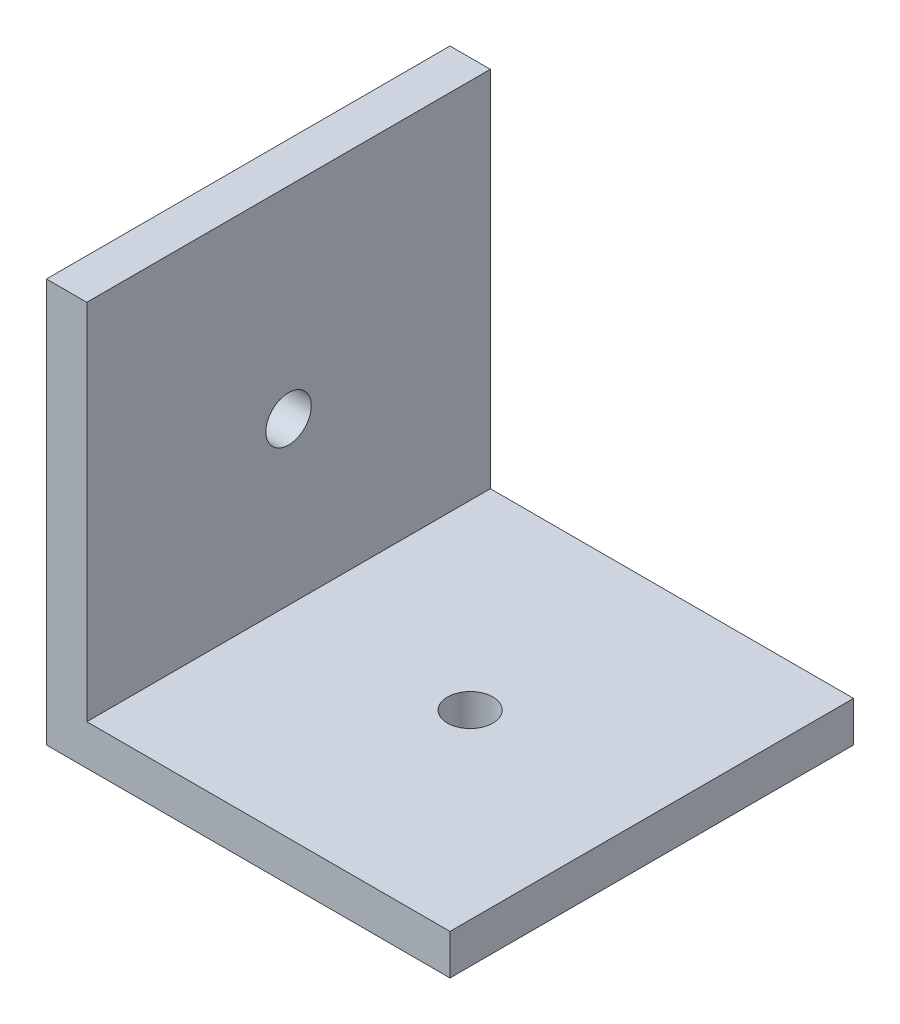
SolidWorks part; units mm, degrees
ref_plane "Plan de face" through (0, 0, 0) normal (0, 0, 1) x (1, 0, 0)
ref_plane "Plan de dessus" through (0, 0, 0) normal (0, 1, 0) x (1, 0, 0)
ref_plane "Plan de droite" through (0, 0, 0) normal (1, 0, 0) x (0, 0, -1)
sketch "Esquisse1" plane through (0, 0, 0) normal (0, 0, 1) x (1, 0, 0)
  line L0 (0, 36) -> (0, 0)
  line L1 (0, 0) -> (36, 0)
  line L2 (36, 0) -> (36, -4)
  line L3 (36, -4) -> (-4, -4)
  line L4 (-4, -4) -> (-4, 36)
  line L5 (-4, 36) -> (0, 36)
  dimension "D1" = 4
  dimension "D2" = 40
  dimension "D3" = 40
extrude "Boss.-Extru.1" add sketch "Esquisse1" along normal blind 40
hole_wizard "Dégagement M41" positions "Esquisse5" profile "Esquisse4" hole size "M4" standard "ISO" end condition through all
sketch "Esquisse5" plane through (0, 0, 0) normal (0, 1, 0) x (1, 0, 0)
  line L0 (36, 0) -> (0, 0) construction
  line L1 (36, -40) -> (36, 0) construction
  point P0 (18, -20)
  dimension "D1" = 20
  dimension "D2" = 18
sketch "Esquisse4" plane through (18, 0, 20) normal (1, 0, 0) x (0, 0, 1)
  line L0 (0, 0) -> (0, 4)
  line L1 (0, 4) -> (2.25, 4)
  line L2 (2.25, 4) -> (2.25, 0)
  line L5 (2.25, 0) -> (0, 0)
  line L11 (0, -6.35) -> (0, 107.95) construction
  dimension "Diamètre du perçage jusqu'au prochain" = 4.5
  dimension "Profondeur du perçage jusqu'au prochain" = 4
hole_wizard "Dégagement M42" positions "Esquisse7" profile "Esquisse6" hole size "M4" standard "ISO" end condition through all
sketch "Esquisse7" plane through (0, 0, 0) normal (1, 0, 0) x (0, 0, -1)
  line L0 (-40, 36) -> (0, 36) construction
  line L1 (-40, 0) -> (-40, 36) construction
  point P0 (-20, 16)
  dimension "D1" = 20
  dimension "D2" = 20
sketch "Esquisse6" plane through (0, 16, 20) normal (0, 1, 0) x (0, 0, -1)
  line L0 (0, 0) -> (0, 4)
  line L1 (0, 4) -> (2.25, 4)
  line L2 (2.25, 4) -> (2.25, 0)
  line L5 (2.25, 0) -> (0, 0)
  line L11 (0, -6.35) -> (0, 107.95) construction
  dimension "Diamètre du perçage jusqu'au prochain" = 4.5
  dimension "Profondeur du perçage jusqu'au prochain" = 4
